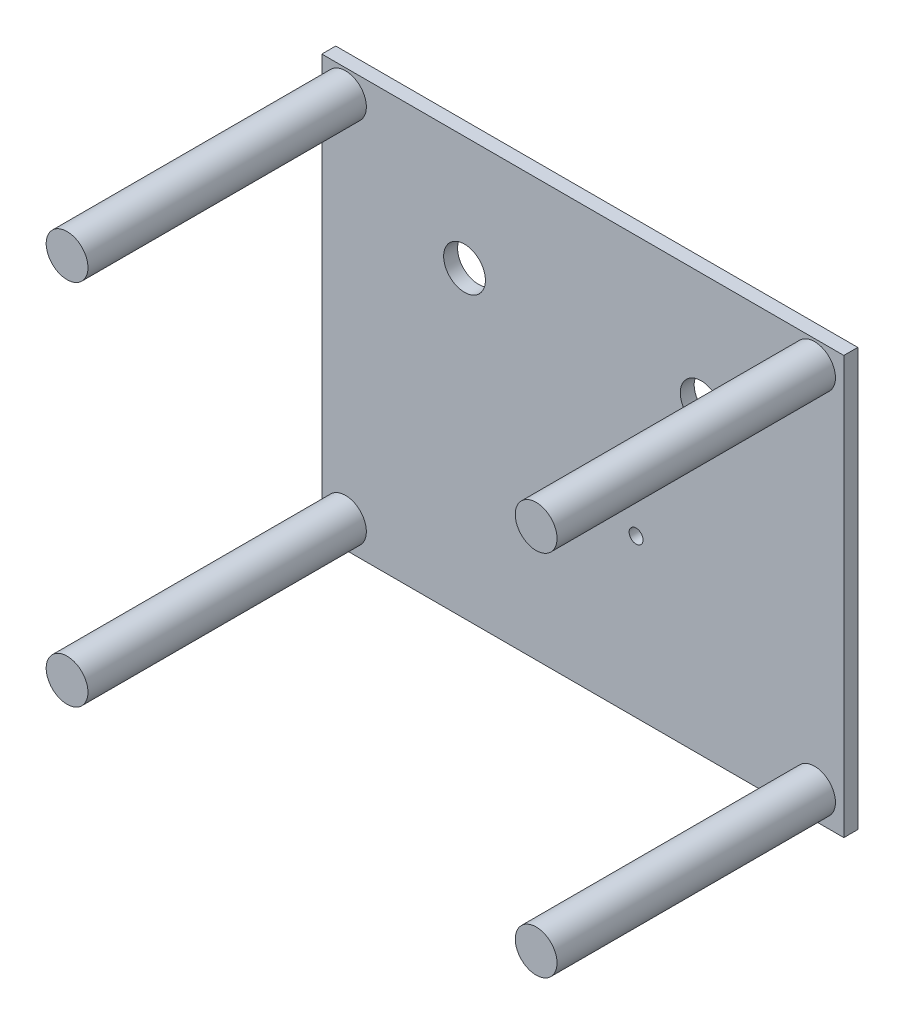
SolidWorks part; units mm, degrees
ref_plane "Plan de face" through (0, 0, 0) normal (0, 0, 1) x (1, 0, 0)
ref_plane "Plan de dessus" through (0, 0, 0) normal (0, 1, 0) x (1, 0, 0)
ref_plane "Plan de droite" through (0, 0, 0) normal (1, 0, 0) x (0, 0, -1)
sketch "Esquisse3" plane through (0, 0, 0) normal (0, 0, 1) x (1, 0, 0)
  line L0 (-17, 13.6) -> (17, 13.6) construction
  line L1 (-37.5, -30) -> (37.5, -30)
  line L2 (-37.5, -30) -> (-37.5, 30)
  line L3 (-37.5, 30) -> (37.5, 30)
  line L4 (37.5, -30) -> (37.5, 30)
  line L5 (-37.5, -30) -> (37.5, 30) construction
  line L6 (-37.5, 30) -> (37.5, -30) construction
  line L7 (17, 13.6) -> (6.0484, -7.4) construction
  circle A0 centre (-17, 13.6) radius 6
  circle A1 centre (17, 13.6) radius 6
  circle A2 centre (6.0484, -7.4) radius 2
  point P0 (0, 0)
  dimension "D4" = 12
  dimension "D5" = 12
  dimension "D6" = 4
  dimension "D1" = 75
  dimension "D2" = 60
  dimension "D3" = 34
  dimension "D7" = 21
extrude "Boss.-Extru.4" add sketch "Esquisse3" along normal blind 2 contours L2 L3 L4 L1
sketch "Esquisse7" plane through (0, 0, 2) normal (0, 0, 1) x (1, 0, 0)
  line L0 (-17, 13.6) -> (17, 13.6) construction
  line L1 (-37.5, 30) -> (37.5, 30) construction
  line L2 (37.5, -30) -> (37.5, 30) construction
  line L5 (-37.5, -30) -> (37.5, 30) construction
  line L6 (-37.5, 30) -> (37.5, -30) construction
  line L7 (17, 13.6) -> (7.6492, -7.4) construction
  circle A0 centre (-17, 13.6) radius 3
  circle A1 centre (17, 13.6) radius 3
  circle A2 centre (7.6492, -7.4) radius 1
  point P0 (0, 0)
  dimension "D4" = 6
  dimension "D5" = 6
  dimension "D6" = 2
  dimension "D1" = 75
  dimension "D2" = 60
  dimension "D3" = 34
  dimension "D7" = 21
extrude "Enlèv. mat.-Extru.1" cut sketch "Esquisse7" against normal blind 2 contours A2 | A1 | A0
sketch "Esquisse8" plane through (0, 0, 0) normal (0, 0, -1) x (-1, 0, 0)
sketch "Esquisse9" plane through (0, 0, 2) normal (0, 0, 1) x (1, 0, 0)
  circle A0 centre (-34.1013, 26.6176) radius 3
  circle A1 centre (33.2923, 26.6176) radius 3
  circle A2 centre (33.2923, -26.2131) radius 3
  circle A3 centre (-34.1013, -26.2131) radius 3
  dimension "D1" = 6
  dimension "D2" = 6
  dimension "D3" = 6
  dimension "D4" = 6
extrude "Boss.-Extru.5" add sketch "Esquisse9" along normal blind 40
